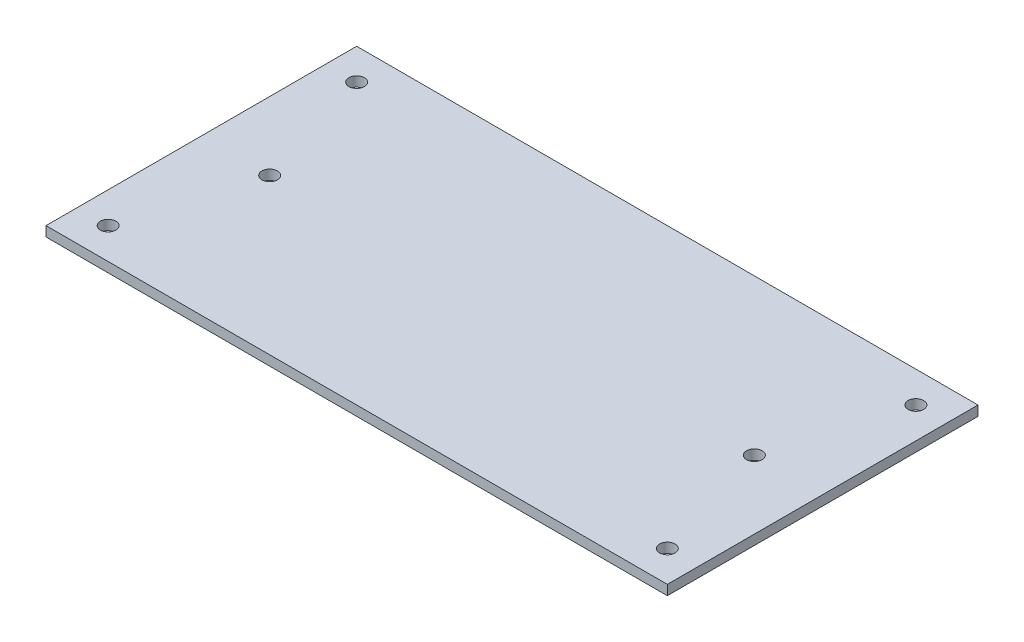
SolidWorks part; units mm, degrees
ref_plane "Front Plane" through (0, 0, 0) normal (0, 0, 1) x (1, 0, 0)
ref_plane "Top Plane" through (0, 0, 0) normal (0, 1, 0) x (1, 0, 0)
ref_plane "Right Plane" through (0, 0, 0) normal (1, 0, 0) x (0, 0, -1)
sketch "Sketch1" plane through (0, 0, 0) normal (0, 1, 0) x (1, 0, 0)
  line L1 (-100, -50) -> (100, -50)
  line L2 (-100, -50) -> (-100, 50)
  line L3 (-100, 50) -> (100, 50)
  line L4 (100, -50) -> (100, 50)
  line L5 (-100, -50) -> (100, 50) construction
  line L6 (-100, 50) -> (100, -50) construction
  line L7 (-60.25, 32) -> (60.25, 32)
  line L8 (-60.25, 32) -> (-60.25, -32)
  line L9 (-60.25, -32) -> (60.25, -32)
  line L10 (60.25, 32) -> (60.25, -32)
  line L11 (-60.25, 32) -> (60.25, -32) construction
  line L12 (-60.25, -32) -> (60.25, 32) construction
  line L13 (-16.5, 0) -> (16.5, 0) construction
  line L14 (0, -16.5) -> (0, 16.5) construction
  circle A0 centre (-90, 40) radius 2.5
  circle A1 centre (-90, -40) radius 2.5
  circle A2 centre (90, 40) radius 2.5
  circle A3 centre (90, -40) radius 2.5
  point P0 (0, 0)
  point P6 (0, 0)
  point P23 (-65, -40)
  dimension "D7" = 5
  dimension "D1" = 100
  dimension "D2" = 200
  dimension "D3" = 120.5
  dimension "D4" = 64
  dimension "D5" = 10
  dimension "D6" = 10
extrude "Boss-Extrude1" add sketch "Sketch1" along normal blind 3.175 contours L1 L4 L3 L2 A3 A1 A0 L7 L10 L9 L8 A2 | L10 L7 L8 L9
sketch "Sketch2" plane through (0, 3.175, 0) normal (0, 1, 0) x (1, 0, 0)
  line L0 (-55, 0) -> (55, 0) construction
  line L1 (0, -55) -> (0, 55) construction
  circle A0 centre (-78, 0) radius 2.5
  circle A1 centre (78, 0) radius 2.5
  dimension "D1" = 5
  dimension "D2" = 78
extrude "Cut-Extrude1" cut sketch "Sketch2" against normal through all
